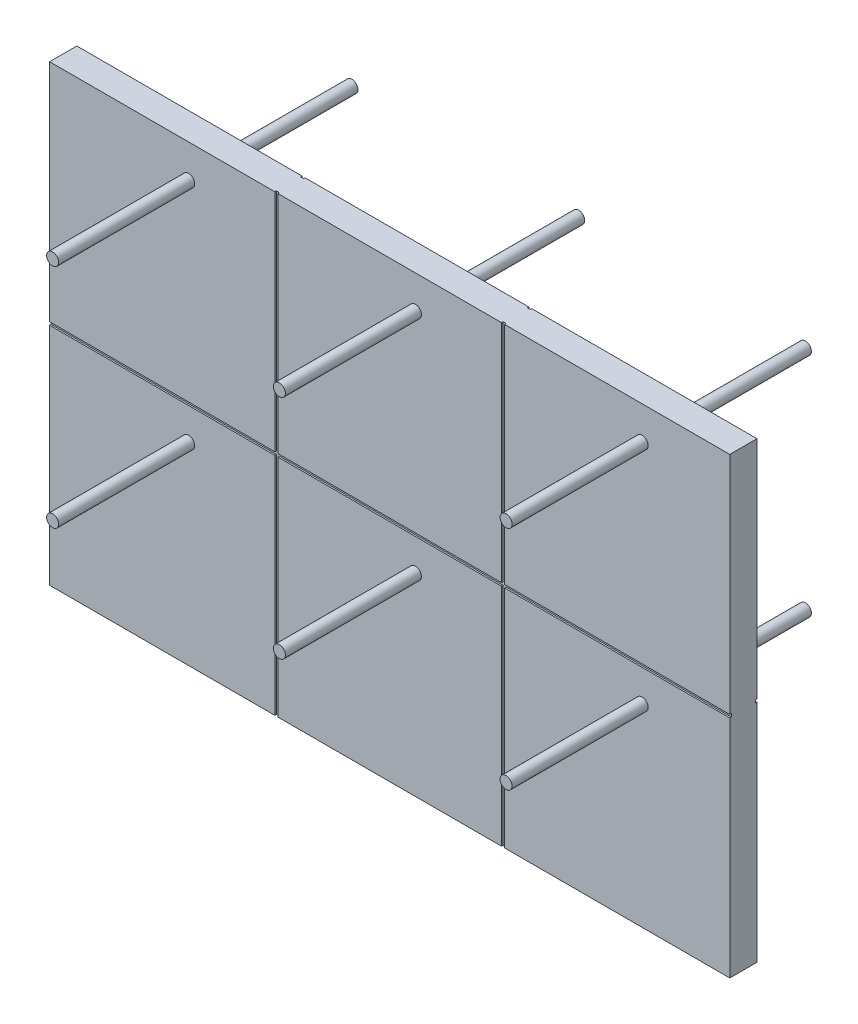
SolidWorks part; units mm, degrees
ref_plane "Front Plane" through (0, 0, 0) normal (0, 0, 1) x (1, 0, 0)
ref_plane "Top Plane" through (0, 0, 0) normal (0, 1, 0) x (1, 0, 0)
ref_plane "Right Plane" through (0, 0, 0) normal (1, 0, 0) x (0, 0, -1)
sketch "Sketch1" plane through (0, 0, 0) normal (0, 0, 1) x (1, 0, 0)
  line L1 (-225, 150) -> (225, 150)
  line L2 (-225, 150) -> (-225, -150)
  line L3 (-225, -150) -> (225, -150)
  line L4 (225, 150) -> (225, -150)
  line L5 (-225, 150) -> (225, -150) construction
  line L6 (-225, -150) -> (225, 150) construction
  point P0 (0, 0)
  dimension "D1" = 300
  dimension "D2" = 450
extrude "Boss-Extrude1" add sketch "Sketch1" along normal mid plane 18
sketch "Sketch3" plane through (0, 0, 9) normal (0, 0, 1) x (1, 0, 0)
  line L0 (-225, 150) -> (-75, 150) construction
  line L1 (225, 150) -> (-225, 150) construction
  line L2 (-75, 150) -> (75, 150) construction
  line L3 (75, 150) -> (225, 150) construction
  line L4 (225, -150) -> (225, 150) construction
  line L5 (225, 150) -> (225, 0) construction
  line L6 (225, 0) -> (225, -150) construction
  line L7 (-225, 1) -> (-225, -1)
  line L9 (-76, 150) -> (-76, 1)
  line L10 (74, -1) -> (74, -150)
  line L11 (74, 150) -> (74, 1)
  line L12 (76, -1) -> (76, -150)
  line L14 (225, 1) -> (76, 1)
  line L15 (-74, 150) -> (-74, 1)
  line L16 (76, 150) -> (76, 1)
  line L17 (225, -1) -> (76, -1)
  line L18 (74, 1) -> (-74, 1)
  line L19 (74, -1) -> (-74, -1)
  line L20 (-76, -1) -> (-76, -150)
  line L21 (-76, 150) -> (-74, 150)
  line L22 (74, 150) -> (76, 150)
  line L23 (225, 1) -> (225, -1)
  line L24 (-74, -1) -> (-74, -150)
  line L25 (74, -150) -> (76, -150)
  line L26 (-76, -1) -> (-225, -1)
  line L27 (-76, 1) -> (-225, 1)
  line L28 (-76, -150) -> (-74, -150)
extrude "Cut-Extrude2" cut sketch "Sketch3" against normal blind 1
sketch "Sketch5" plane through (0, 0, 9) normal (0, 0, 1) x (1, 0, 0)
  line L0 (-76, 150) -> (-225, 150) construction
  line L1 (-225, 150) -> (-225, 1) construction
  circle A0 centre (-133, 128) radius 4
  circle A1 centre (17, 128) radius 4
  circle A2 centre (167, 128) radius 4
  circle A3 centre (17, -22) radius 4
  circle A4 centre (167, -22) radius 4
  circle A5 centre (-133, -22) radius 4
  dimension "D1" = 8
  dimension "D2" = 22
  dimension "D3" = 92
  dimension "D4" = 3
  dimension "D5" = 2
extrude "Boss-Extrude3" add sketch "Sketch5" along normal blind 90
mirror "Mirror1" about plane through (0, 0, 0) normal (0, 0, 1) of "Boss-Extrude3", "Cut-Extrude2"
